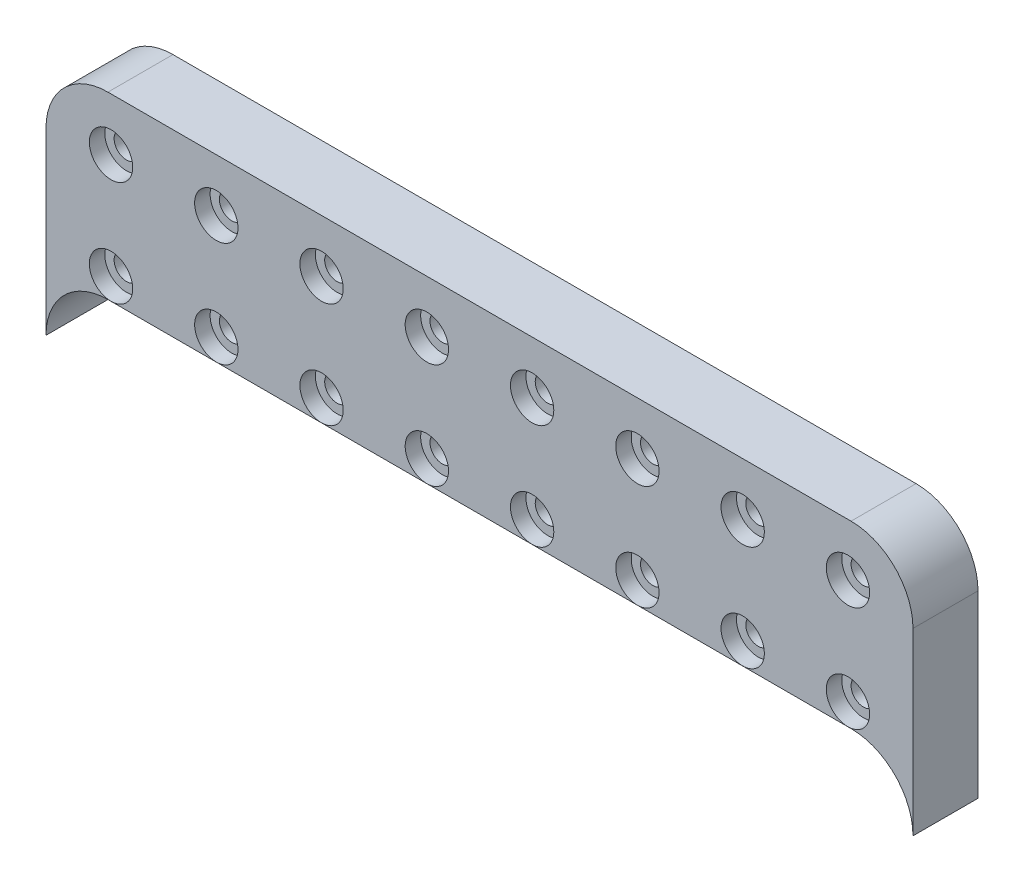
SolidWorks part; units mm, degrees
ref_plane "Ebene vorne" through (0, 0, 0) normal (0, 0, 1) x (1, 0, 0)
ref_plane "Ebene oben" through (0, 0, 0) normal (0, 1, 0) x (1, 0, 0)
ref_plane "Ebene rechts" through (0, 0, 0) normal (1, 0, 0) x (0, 0, -1)
sketch "Skizze1" plane through (0, 0, 0) normal (0, 0, 1) x (1, 0, 0)
  line L1 (0, 0) -> (140, 0)
  line L2 (0, 0) -> (0, 180)
  line L3 (0, 180) -> (140, 180)
  line L4 (140, 0) -> (140, 180)
  dimension "D1" = 180
  dimension "D2" = 140
extrude "Aufsatz-Linear austragen1" add sketch "Skizze1" along normal blind 10.5
sketch "Skizze2" plane through (0, 0, 10.5) normal (0, 0, 1) x (1, 0, 0)
  line L4 (0, 0) -> (140, 0) construction
  line L5 (70, 180) -> (70, 0) construction
  line L6 (140, 180) -> (0, 180) construction
  line L7 (0, 90) -> (140, 90) construction
  line L8 (0, 180) -> (0, 0) construction
  line L9 (140, 0) -> (140, 180) construction
  circle A0 centre (10.5, 183.5) radius 3.5
  circle A1 centre (27.5, 183.5) radius 3.5
  circle A2 centre (44.5, 183.5) radius 3.5
  circle A3 centre (61.5, 183.5) radius 3.5
  circle A4 centre (78.5, 183.5) radius 3.5
  circle A5 centre (95.5, 183.5) radius 3.5
  circle A6 centre (112.5, 183.5) radius 3.5
  circle A7 centre (129.5, 183.5) radius 3.5
  circle A8 centre (27.5, 166.5) radius 3.5
  circle A9 centre (44.5, 166.5) radius 3.5
  circle A10 centre (61.5, 166.5) radius 3.5
  circle A11 centre (78.5, 166.5) radius 3.5
  circle A12 centre (95.5, 166.5) radius 3.5
  circle A13 centre (112.5, 166.5) radius 3.5
  circle A14 centre (129.5, 166.5) radius 3.5
  circle A15 centre (27.5, 149.5) radius 3.5
  circle A16 centre (44.5, 149.5) radius 3.5
  circle A17 centre (61.5, 149.5) radius 3.5
  circle A18 centre (78.5, 149.5) radius 3.5
  circle A19 centre (95.5, 149.5) radius 3.5
  circle A20 centre (112.5, 149.5) radius 3.5
  circle A21 centre (129.5, 149.5) radius 3.5
  circle A22 centre (27.5, 132.5) radius 3.5
  circle A23 centre (44.5, 132.5) radius 3.5
  circle A24 centre (61.5, 132.5) radius 3.5
  circle A25 centre (78.5, 132.5) radius 3.5
  circle A26 centre (95.5, 132.5) radius 3.5
  circle A27 centre (112.5, 132.5) radius 3.5
  circle A28 centre (129.5, 132.5) radius 3.5
  circle A29 centre (27.5, 115.5) radius 3.5
  circle A30 centre (44.5, 115.5) radius 3.5
  circle A31 centre (61.5, 115.5) radius 3.5
  circle A32 centre (78.5, 115.5) radius 3.5
  circle A33 centre (95.5, 115.5) radius 3.5
  circle A34 centre (112.5, 115.5) radius 3.5
  circle A35 centre (129.5, 115.5) radius 3.5
  circle A36 centre (27.5, 98.5) radius 3.5
  circle A37 centre (44.5, 98.5) radius 3.5
  circle A38 centre (61.5, 98.5) radius 3.5
  circle A39 centre (78.5, 98.5) radius 3.5
  circle A40 centre (95.5, 98.5) radius 3.5
  circle A41 centre (112.5, 98.5) radius 3.5
  circle A42 centre (129.5, 98.5) radius 3.5
  circle A43 centre (27.5, 81.5) radius 3.5
  circle A44 centre (44.5, 81.5) radius 3.5
  circle A45 centre (61.5, 81.5) radius 3.5
  circle A46 centre (78.5, 81.5) radius 3.5
  circle A47 centre (95.5, 81.5) radius 3.5
  circle A48 centre (112.5, 81.5) radius 3.5
  circle A49 centre (129.5, 81.5) radius 3.5
  circle A50 centre (27.5, 64.5) radius 3.5
  circle A51 centre (44.5, 64.5) radius 3.5
  circle A52 centre (61.5, 64.5) radius 3.5
  circle A53 centre (78.5, 64.5) radius 3.5
  circle A54 centre (95.5, 64.5) radius 3.5
  circle A55 centre (112.5, 64.5) radius 3.5
  circle A56 centre (129.5, 64.5) radius 3.5
  circle A57 centre (27.5, 47.5) radius 3.5
  circle A58 centre (44.5, 47.5) radius 3.5
  circle A59 centre (61.5, 47.5) radius 3.5
  circle A60 centre (78.5, 47.5) radius 3.5
  circle A61 centre (95.5, 47.5) radius 3.5
  circle A62 centre (112.5, 47.5) radius 3.5
  circle A63 centre (129.5, 47.5) radius 3.5
  circle A64 centre (27.5, 30.5) radius 3.5
  circle A65 centre (44.5, 30.5) radius 3.5
  circle A66 centre (61.5, 30.5) radius 3.5
  circle A67 centre (78.5, 30.5) radius 3.5
  circle A68 centre (95.5, 30.5) radius 3.5
  circle A69 centre (112.5, 30.5) radius 3.5
  circle A70 centre (129.5, 30.5) radius 3.5
  circle A71 centre (27.5, 13.5) radius 3.5
  circle A72 centre (44.5, 13.5) radius 3.5
  circle A73 centre (61.5, 13.5) radius 3.5
  circle A74 centre (78.5, 13.5) radius 3.5
  circle A75 centre (95.5, 13.5) radius 3.5
  circle A76 centre (112.5, 13.5) radius 3.5
  circle A77 centre (129.5, 13.5) radius 3.5
  circle A85 centre (10.5, 166.5) radius 3.5
  circle A86 centre (10.5, 149.5) radius 3.5
  circle A87 centre (10.5, 132.5) radius 3.5
  circle A88 centre (10.5, 115.5) radius 3.5
  circle A89 centre (10.5, 98.5) radius 3.5
  circle A90 centre (10.5, 81.5) radius 3.5
  circle A91 centre (10.5, 64.5) radius 3.5
  circle A92 centre (10.5, 47.5) radius 3.5
  circle A93 centre (10.5, 30.5) radius 3.5
  circle A94 centre (10.5, 13.5) radius 3.5
  dimension "D1" = 7
  dimension "D2" = 17
  dimension "D3" = 17
  dimension "D4" = 8
  dimension "D5" = 11
extrude "Schnitt-Linear austragen3" cut sketch "Skizze2" against normal blind 2.5
sketch "Skizze3" plane through (0, 0, 0) normal (0, 0, 1) x (1, 0, 0)
  line L0 (140, 0) -> (140, 180) construction
  line L1 (140, 180) -> (0, 180) construction
  line L5 (70, 200) -> (70, 0) construction
  line L7 (0, 90) -> (140, 90) construction
  circle A0 centre (10.5, 183.5) radius 2
  circle A1 centre (27.5, 183.5) radius 2
  circle A2 centre (44.5, 183.5) radius 2
  circle A3 centre (61.5, 183.5) radius 2
  circle A4 centre (78.5, 183.5) radius 2
  circle A5 centre (95.5, 183.5) radius 2
  circle A6 centre (112.5, 183.5) radius 2
  circle A7 centre (129.5, 183.5) radius 2
  circle A8 centre (27.5, 166.5) radius 2
  circle A9 centre (44.5, 166.5) radius 2
  circle A10 centre (61.5, 166.5) radius 2
  circle A11 centre (78.5, 166.5) radius 2
  circle A12 centre (95.5, 166.5) radius 2
  circle A13 centre (112.5, 166.5) radius 2
  circle A14 centre (129.5, 166.5) radius 2
  circle A15 centre (27.5, 149.5) radius 2
  circle A16 centre (44.5, 149.5) radius 2
  circle A17 centre (61.5, 149.5) radius 2
  circle A18 centre (78.5, 149.5) radius 2
  circle A19 centre (95.5, 149.5) radius 2
  circle A20 centre (112.5, 149.5) radius 2
  circle A21 centre (129.5, 149.5) radius 2
  circle A22 centre (27.5, 132.5) radius 2
  circle A23 centre (44.5, 132.5) radius 2
  circle A24 centre (61.5, 132.5) radius 2
  circle A25 centre (78.5, 132.5) radius 2
  circle A26 centre (95.5, 132.5) radius 2
  circle A27 centre (112.5, 132.5) radius 2
  circle A28 centre (129.5, 132.5) radius 2
  circle A29 centre (27.5, 115.5) radius 2
  circle A30 centre (44.5, 115.5) radius 2
  circle A31 centre (61.5, 115.5) radius 2
  circle A32 centre (78.5, 115.5) radius 2
  circle A33 centre (95.5, 115.5) radius 2
  circle A34 centre (112.5, 115.5) radius 2
  circle A35 centre (129.5, 115.5) radius 2
  circle A36 centre (27.5, 98.5) radius 2
  circle A37 centre (44.5, 98.5) radius 2
  circle A38 centre (61.5, 98.5) radius 2
  circle A39 centre (78.5, 98.5) radius 2
  circle A40 centre (95.5, 98.5) radius 2
  circle A41 centre (112.5, 98.5) radius 2
  circle A42 centre (129.5, 98.5) radius 2
  circle A43 centre (27.5, 81.5) radius 2
  circle A44 centre (44.5, 81.5) radius 2
  circle A45 centre (61.5, 81.5) radius 2
  circle A46 centre (78.5, 81.5) radius 2
  circle A47 centre (95.5, 81.5) radius 2
  circle A48 centre (112.5, 81.5) radius 2
  circle A49 centre (129.5, 81.5) radius 2
  circle A50 centre (27.5, 64.5) radius 2
  circle A51 centre (44.5, 64.5) radius 2
  circle A52 centre (61.5, 64.5) radius 2
  circle A53 centre (78.5, 64.5) radius 2
  circle A54 centre (95.5, 64.5) radius 2
  circle A55 centre (112.5, 64.5) radius 2
  circle A56 centre (129.5, 64.5) radius 2
  circle A57 centre (27.5, 47.5) radius 2
  circle A58 centre (44.5, 47.5) radius 2
  circle A59 centre (61.5, 47.5) radius 2
  circle A60 centre (78.5, 47.5) radius 2
  circle A61 centre (95.5, 47.5) radius 2
  circle A62 centre (112.5, 47.5) radius 2
  circle A63 centre (129.5, 47.5) radius 2
  circle A64 centre (27.5, 30.5) radius 2
  circle A65 centre (44.5, 30.5) radius 2
  circle A66 centre (61.5, 30.5) radius 2
  circle A67 centre (78.5, 30.5) radius 2
  circle A68 centre (95.5, 30.5) radius 2
  circle A69 centre (112.5, 30.5) radius 2
  circle A70 centre (129.5, 30.5) radius 2
  circle A71 centre (27.5, 13.5) radius 2
  circle A72 centre (44.5, 13.5) radius 2
  circle A73 centre (61.5, 13.5) radius 2
  circle A74 centre (78.5, 13.5) radius 2
  circle A75 centre (95.5, 13.5) radius 2
  circle A76 centre (112.5, 13.5) radius 2
  circle A77 centre (129.5, 13.5) radius 2
  circle A78 centre (27.5, -3.5) radius 2
  circle A79 centre (44.5, -3.5) radius 2
  circle A80 centre (61.5, -3.5) radius 2
  circle A81 centre (78.5, -3.5) radius 2
  circle A82 centre (95.5, -3.5) radius 2
  circle A83 centre (112.5, -3.5) radius 2
  circle A84 centre (129.5, -3.5) radius 2
  circle A85 centre (10.5, 166.5) radius 2
  circle A86 centre (10.5, 149.5) radius 2
  circle A87 centre (10.5, 132.5) radius 2
  circle A88 centre (10.5, 115.5) radius 2
  circle A89 centre (10.5, 98.5) radius 2
  circle A90 centre (10.5, 81.5) radius 2
  circle A91 centre (10.5, 64.5) radius 2
  circle A92 centre (10.5, 47.5) radius 2
  circle A93 centre (10.5, 30.5) radius 2
  circle A94 centre (10.5, 13.5) radius 2
  circle A95 centre (10.5, -3.5) radius 2
  point P199 (140, 90)
  point P202 (70, 180)
  dimension "D1" = 4
  dimension "D3" = 17
  dimension "17" = 17
  dimension "D4" = 8
  dimension "D5" = 12
extrude "Schnitt-Linear austragen5" cut sketch "Skizze3" along normal through all
fillet "Verrundung1" radius 10 4 edges at (140, 0, 5.25) (0, 0, 5.25) (0, 180, 5.25) (140, 180, 5.25)
sketch "Skizze7" plane through (0, 0, 10.5) normal (0, 0, 1) x (1, 0, 0)
  line L0 (0, 0) -> (0, 180) construction
  line L1 (10, 145.99) -> (130, 145.99)
  line L5 (140, 0) -> (140, 180) construction
  line L6 (0, 135.99) -> (0, -21.146)
  line L7 (0, -21.146) -> (140, -23.696)
  line L8 (140, -23.696) -> (140, 135.99)
  line L9 (10, 175) -> (130, 175)
  line L10 (0, 170) -> (0, 10) construction
  line L11 (140, 10) -> (140, 170) construction
  line L12 (0, 165) -> (0, 196.0154)
  line L13 (0, 196.0154) -> (140, 196.0154)
  line L14 (140, 196.0154) -> (140, 165)
  arc A0 (10, 145.99) -> (0, 135.99) centre (10, 135.99) ccw
  arc A1 (130, 145.99) -> (140, 135.99) centre (130, 135.99) cw
  arc A2 (140, 170) -> (130, 180) centre (130, 170) ccw construction
  arc A3 (10, 180) -> (0, 170) centre (10, 170) ccw construction
  arc A4 (10, 175) -> (0, 165) centre (10, 165) ccw
  arc A5 (130, 175) -> (140, 165) centre (130, 165) cw
  dimension "D1" = 3.51
  dimension "D2" = 8.5
extrude "Schnitt-Linear austragen17" cut sketch "Skizze7" against normal through all
